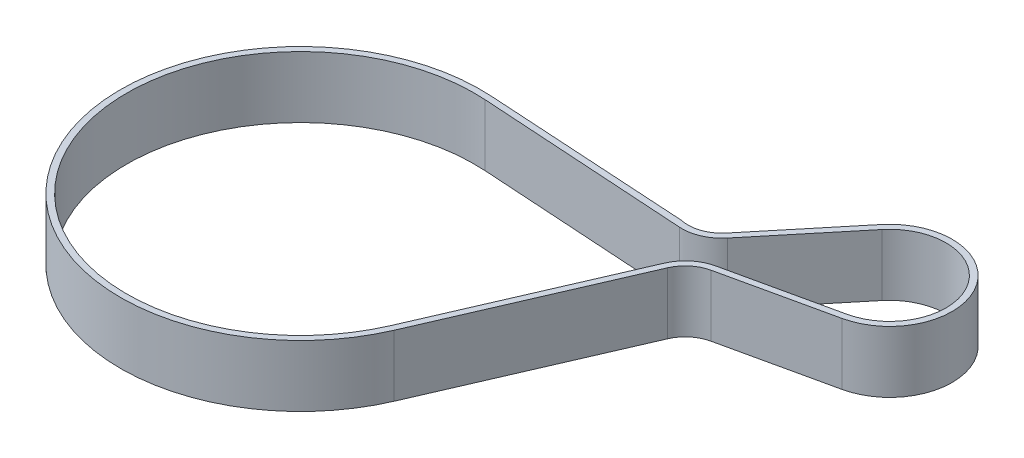
SolidWorks part; units mm, degrees
ref_plane "Front Plane" through (0, 0, 0) normal (0, 0, 1) x (1, 0, 0)
ref_plane "Top Plane" through (0, 0, 0) normal (0, 1, 0) x (1, 0, 0)
ref_plane "Right Plane" through (0, 0, 0) normal (1, 0, 0) x (0, 0, -1)
sketch "Sketch1" plane through (0, 0, 0) normal (0, 1, 0) x (1, 0, 0)
  line L0 (18.6219, 16.2605) -> (29.9995, 30.0446)
  line L1 (21.6016, 11.3923) -> (39.0527, 15.2538)
  line L2 (13.196, 13.9113) -> (-20.5376, 16.059)
  line L3 (17.0413, 7.629) -> (3.6079, -23.3889)
  line L4 (-20.5376, 17.0609) -> (12.3809, 15.0371)
  line L5 (4.5255, -23.7863) -> (17.959, 7.2316)
  line L6 (29.2282, 30.6812) -> (17.8507, 16.8971)
  line L7 (39.2688, 14.2774) -> (21.8177, 10.4159)
  circle A0 centre (37.0715, 24.2072) radius 9.17
  circle A1 centre (13.609, 20.3982) radius 5.5
  circle A2 centre (23.006, 5.0458) radius 5.5
  circle A3 centre (13.609, 20.3982) radius 6.5
  circle A4 centre (23.006, 5.0458) radius 6.5
  circle A5 centre (37.0715, 24.2072) radius 10.17
  circle A6 centre (-22.3338, -12.1539) radius 28.27
  circle A7 centre (-22.3338, -12.1539) radius 29.27
extrude "Boss-Extrude1" add sketch "Sketch1" along normal blind 7 contours A7 L3 A6 L2 | A7 L5 A4 L3 | A7 L2 A3 L4 | A3 L6 A1 L4 | L7 A4 L5 A2 | A5 L1 A4 L7 | A5 L6 A3 L0 | A5 L0 A0 L1
sketch "Sketch2" plane through (0, 7, 0) normal (0, 1, 0) x (1, 0, 0)
  line L0 (17.0413, 7.629) -> (3.6079, -23.3889) construction
  line L1 (21.6016, 11.3923) -> (39.0527, 15.2538) construction
  line L2 (18.6219, 16.2605) -> (29.9995, 30.0446) construction
  line L3 (13.196, 13.9113) -> (-20.5376, 16.059) construction
  line L4 (21.8177, 10.4159) -> (39.2688, 14.2774)
  line L5 (29.2282, 30.6812) -> (17.8507, 16.8971)
  line L6 (12.3809, 15.0371) -> (-20.5376, 17.0609)
  line L7 (4.5255, -23.7863) -> (17.959, 7.2316)
  line L8 (21.8177, 10.4159) -> (39.2688, 14.2774)
  line L9 (29.2282, 30.6812) -> (17.8507, 16.8971)
  line L10 (12.3809, 15.0371) -> (-20.5376, 17.0609)
  line L11 (4.5255, -23.7863) -> (17.959, 7.2316)
  line L12 (17.0413, 7.629) -> (3.6079, -23.3889)
  line L13 (21.6016, 11.3923) -> (39.0527, 15.2538)
  line L14 (18.6219, 16.2605) -> (29.9995, 30.0446)
  line L15 (13.196, 13.9113) -> (-20.5376, 16.059)
  arc A0 (21.6016, 11.3923) -> (17.0413, 7.629) centre (23.006, 5.0458) ccw construction
  arc A1 (39.0527, 15.2538) -> (29.9995, 30.0446) centre (37.0715, 24.2072) ccw construction
  arc A2 (13.196, 13.9113) -> (18.6219, 16.2605) centre (13.609, 20.3982) ccw construction
  arc A3 (-20.5376, 16.059) -> (3.6079, -23.3889) centre (-22.3338, -12.1539) ccw construction
  arc A4 (39.2688, 14.2774) -> (29.2282, 30.6812) centre (37.0715, 24.2072) ccw
  arc A5 (12.3809, 15.0371) -> (17.8507, 16.8971) centre (13.609, 20.3982) ccw
  arc A6 (-20.5376, 17.0609) -> (4.5255, -23.7863) centre (-22.3338, -12.1539) ccw
  arc A7 (21.8177, 10.4159) -> (17.959, 7.2316) centre (23.006, 5.0458) ccw
  arc A8 (39.2688, 14.2774) -> (29.2282, 30.6812) centre (37.0715, 24.2072) ccw
  arc A9 (12.3809, 15.0371) -> (17.8507, 16.8971) centre (13.609, 20.3982) ccw
  arc A10 (-20.5376, 17.0609) -> (4.5255, -23.7863) centre (-22.3338, -12.1539) ccw
  arc A11 (21.8177, 10.4159) -> (17.959, 7.2316) centre (23.006, 5.0458) ccw
  arc A12 (21.6016, 11.3923) -> (17.0413, 7.629) centre (23.006, 5.0458) ccw
  arc A13 (39.0527, 15.2538) -> (29.9995, 30.0446) centre (37.0715, 24.2072) ccw
  arc A14 (13.196, 13.9113) -> (18.6219, 16.2605) centre (13.609, 20.3982) ccw
  arc A15 (-20.5376, 16.059) -> (3.6079, -23.3889) centre (-22.3338, -12.1539) ccw
  dimension "D1" = 0
extrude "Boss-Extrude2" add sketch "Sketch2" along normal blind 3
